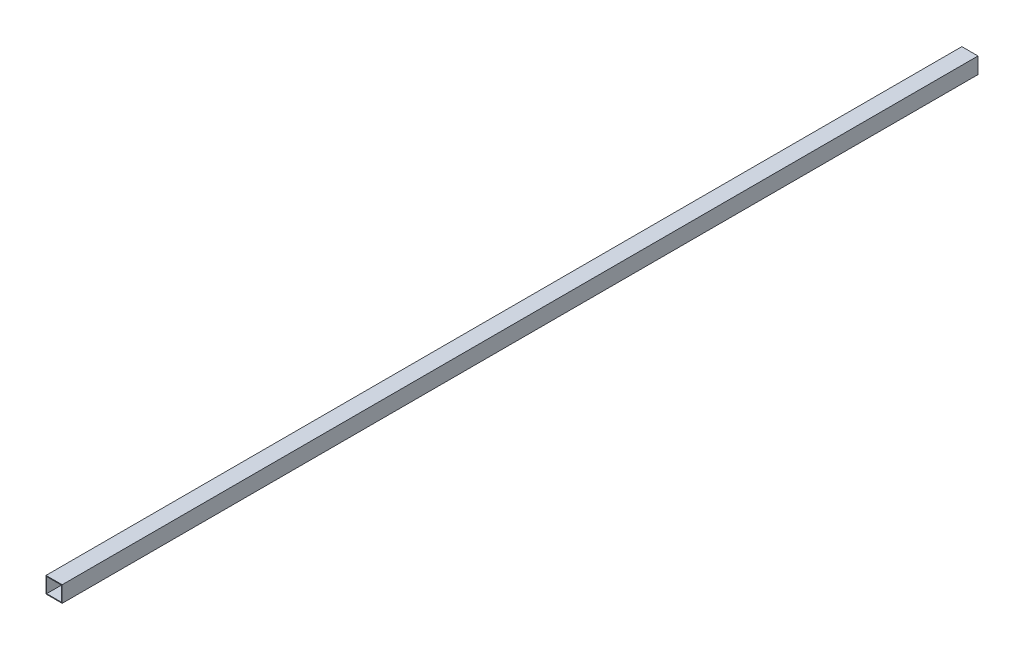
SolidWorks part; units mm, degrees
material "Plain Carbon Steel"
ref_plane "Front Plane" through (0, 0, 0) normal (0, 0, 1) x (1, 0, 0)
ref_plane "Top Plane" through (0, 0, 0) normal (0, 1, 0) x (1, 0, 0)
ref_plane "Right Plane" through (0, 0, 0) normal (1, 0, 0) x (0, 0, -1)
sketch "Sketch2" plane through (0, 0, 0) normal (0, 0, 1) x (1, 0, 0)
  line L0 (0, 19.05) -> (1.5875, 19.05) construction
  line L1 (0, 0) -> (38.1, 0)
  line L2 (0, 0) -> (0, 38.1)
  line L3 (0, 38.1) -> (38.1, 38.1)
  line L4 (38.1, 0) -> (38.1, 38.1)
  line L5 (1.5875, 1.5875) -> (36.5125, 1.5875)
  line L6 (1.5875, 1.5875) -> (1.5875, 36.5125)
  line L7 (1.5875, 36.5125) -> (36.5125, 36.5125)
  line L8 (36.5125, 1.5875) -> (36.5125, 36.5125)
  line L9 (19.05, 36.5125) -> (19.05, 38.1) construction
  line L10 (36.5125, 19.05) -> (38.1, 19.05) construction
  line L11 (19.05, 0) -> (19.05, 1.5875) construction
  dimension "D1" = 38.1
  dimension "D2" = 1.5875
  dimension "D3" = 38.1
extrude "Boss-Extrude1" add sketch "Sketch2" along normal blind 2159
